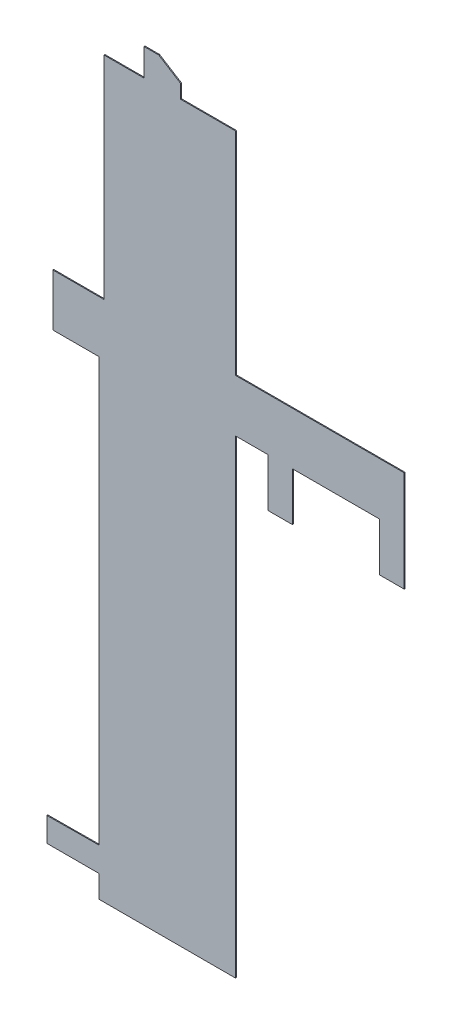
SolidWorks part; units mm, degrees
ref_plane "前视基准面" through (0, 0, 0) normal (0, 0, 1) x (1, 0, 0)
ref_plane "上视基准面" through (0, 0, 0) normal (0, 1, 0) x (1, 0, 0)
ref_plane "右视基准面" through (0, 0, 0) normal (1, 0, 0) x (0, 0, -1)
ref_plane "基准面4"
sketch "草图1" plane through (0, 0, 42) normal (0, 0, 1) x (1, 0, 0)
  line L0 (442.5, -384.2) -> (458.5, -384.2)
  line L1 (458.5, -384.2) -> (458.5, -354.2)
  line L2 (458.5, -354.2) -> (442.5, -354.2)
  line L3 (442.5, -354.2) -> (442.5, -384.2)
  line L4 (398.5, -384.2) -> (400.5, -384.2)
  line L5 (400.5, -384.2) -> (400.5, -354.2)
  line L6 (400.5, -354.2) -> (384.5, -354.2)
  line L7 (384.5, -354.2) -> (384.5, -384.2)
  line L8 (384.5, -384.2) -> (398.5, -384.2)
  line L9 (700.5, -673.6) -> (700.5, -726.6)
  line L10 (700.5, -726.6) -> (727.5, -726.6)
  line L11 (727.5, -726.6) -> (727.5, -673.6)
  line L12 (727.5, -673.6) -> (700.5, -673.6)
  line L13 (578, -673.6) -> (578, -726.6)
  line L14 (578, -726.6) -> (605, -726.6)
  line L15 (605, -726.6) -> (605, -673.6)
  line L16 (605, -673.6) -> (578, -673.6)
  line L17 (482.5, -443.7) -> (542.5, -443.7)
  line L18 (542.5, -443.7) -> (542.5, -413.6)
  line L19 (542.5, -413.6) -> (501.5, -413.6)
  line L20 (501.5, -413.6) -> (501.5, -423.1)
  line L21 (501.5, -423.1) -> (482.5, -423.1)
  line L22 (482.5, -423.1) -> (482.5, -443.7)
  line L23 (501.5, -413.6) -> (542.5, -413.6)
  line L24 (542.5, -413.6) -> (542.5, -384.2)
  line L25 (542.5, -384.2) -> (482.5, -384.2)
  line L26 (482.5, -384.2) -> (482.5, -410.1)
  line L27 (482.5, -410.1) -> (501.5, -410.1)
  line L28 (501.5, -410.1) -> (501.5, -413.6)
  line L29 (482.5, -498.7) -> (542.5, -498.7)
  line L30 (542.5, -498.7) -> (542.5, -443.7)
  line L31 (542.5, -443.7) -> (482.5, -443.7)
  line L32 (482.5, -443.7) -> (482.5, -498.7)
  line L33 (398.5, -499.2) -> (458.5, -499.2)
  line L34 (458.5, -499.2) -> (458.5, -441.7)
  line L35 (458.5, -441.7) -> (398.5, -441.7)
  line L36 (398.5, -441.7) -> (398.5, -499.2)
  line L37 (398.5, -441.7) -> (458.5, -441.7)
  line L38 (458.5, -441.7) -> (458.5, -384.2)
  line L39 (458.5, -384.2) -> (442.5, -384.2)
  line L40 (442.5, -384.2) -> (400.5, -384.2)
  line L41 (400.5, -384.2) -> (398.5, -384.2)
  line L42 (398.5, -384.2) -> (398.5, -441.7)
  line L43 (398.5, -616.2) -> (458.5, -616.2)
  line L44 (458.5, -616.2) -> (458.5, -499.2)
  line L45 (458.5, -499.2) -> (398.5, -499.2)
  line L46 (398.5, -499.2) -> (398.5, -616.2)
  line L47 (542.5, -616.2) -> (542.5, -498.7)
  line L48 (542.5, -498.7) -> (482.5, -498.7)
  line L49 (482.5, -498.7) -> (482.5, -616.2)
  line L50 (482.5, -616.2) -> (542.5, -616.2)
  line L51 (542.5, -1127.7) -> (417, -1127.7)
  line L52 (417, -1127.7) -> (417, -1188.1)
  line L53 (417, -1188.1) -> (542.5, -1188.1)
  line L54 (542.5, -1188.1) -> (542.5, -1127.7)
  line L55 (542.5, -786.2) -> (417.2959, -786.2)
  line L56 (417.2959, -786.2) -> (417, -896.8)
  line L57 (417, -896.8) -> (542.5, -896.8)
  line L58 (542.5, -896.8) -> (542.5, -786.2)
  line L59 (393, -673.2) -> (393, -1136.7)
  line L60 (393, -1136.7) -> (336, -1137.1)
  line L61 (336, -1137.1) -> (336, -1163.6)
  line L62 (336, -1163.6) -> (393, -1163.6)
  line L63 (393, -1163.6) -> (393, -1188.1)
  line L64 (393, -1188.1) -> (417, -1188.1)
  line L65 (417, -1188.1) -> (417, -1127.7)
  line L66 (417, -1127.7) -> (417, -896.8)
  line L67 (417, -896.8) -> (417.2959, -786.2)
  line L68 (417.2959, -786.2) -> (417.5981, -673.2658)
  line L69 (417.5981, -673.2658) -> (393, -673.2)
  line L70 (417.5981, -673.2658) -> (417.2959, -786.2)
  line L71 (417.2959, -786.2) -> (542.5, -786.2)
  line L72 (542.5, -786.2) -> (542.5, -673.6)
  line L73 (542.5, -673.6) -> (417.5981, -673.2658)
  line L74 (542.5, -896.8) -> (417, -896.8)
  line L75 (417, -896.8) -> (417, -1127.7)
  line L76 (417, -1127.7) -> (542.5, -1127.7)
  line L77 (542.5, -1127.7) -> (542.5, -896.8)
  line L78 (342.5, -616.2) -> (192.5, -616.2)
  line L79 (192.5, -616.2) -> (146.7, -616.2)
  line L80 (146.7, -616.2) -> (146.7, -566.2)
  line L81 (146.7, -566.2) -> (142.9, -566.2)
  line L82 (142.9, -566.2) -> (83.4, -566.2)
  line L83 (83.4, -566.2) -> (83.4, -463)
  line L84 (83.4, -463) -> (83.4, -379.5)
  line L85 (83.4, -379.5) -> (83.4, -276.5)
  line L86 (83.4, -276.5) -> (83.4, -137.6)
  line L87 (83.4, -137.6) -> (118.4, -137.6)
  line L88 (118.4, -137.6) -> (118.4, -79.7)
  line L89 (118.4, -79.7) -> (83.4, -79.7)
  line L90 (83.4, -79.7) -> (83.4, -23.7)
  line L91 (83.4, -23.7) -> (118.4, -23.7)
  line L92 (118.4, -23.7) -> (118.4, 0)
  line L93 (118.4, 0) -> (60, 0)
  line L94 (60, 0) -> (60, -80.6)
  line L95 (60, -80.6) -> (60, -191.9)
  line L96 (60, -191.9) -> (60, -276.5)
  line L97 (60, -276.5) -> (60, -335.9)
  line L98 (60, -335.9) -> (60, -420.6)
  line L99 (60, -420.6) -> (60, -550.6)
  line L100 (60, -550.6) -> (60, -677.8)
  line L101 (60, -677.8) -> (60, -782.9)
  line L102 (60, -782.9) -> (60, -839.5)
  line L103 (60, -839.5) -> (60, -923.6)
  line L104 (60, -923.6) -> (60, -1007.7)
  line L105 (60, -1007.7) -> (60, -1091.2)
  line L106 (60, -1091.2) -> (60, -1169.8)
  line L107 (60, -1169.8) -> (188.1, -1169.8)
  line L108 (188.1, -1169.8) -> (188.1, -1163.6)
  line L109 (188.1, -1163.6) -> (188.1, -1137.1)
  line L110 (188.1, -1137.1) -> (336, -1137.1)
  line L111 (336, -1137.1) -> (393, -1136.7)
  line L112 (393, -1136.7) -> (393, -673.2)
  line L113 (393, -673.2) -> (417.5981, -673.2658)
  line L114 (417.5981, -673.2658) -> (542.5, -673.6)
  line L115 (542.5, -673.6) -> (578, -673.6)
  line L116 (578, -673.6) -> (605, -673.6)
  line L117 (605, -673.6) -> (700.5, -673.6)
  line L118 (700.5, -673.6) -> (727.5, -673.6)
  line L119 (727.5, -673.6) -> (727.5, -616.2)
  line L120 (727.5, -616.2) -> (542.5, -616.2)
  line L121 (542.5, -616.2) -> (482.5, -616.2)
  line L122 (482.5, -616.2) -> (482.5, -498.7)
  line L123 (482.5, -498.7) -> (482.5, -443.7)
  line L124 (482.5, -443.7) -> (482.5, -423.1)
  line L125 (482.5, -423.1) -> (501.5, -423.1)
  line L126 (501.5, -423.1) -> (501.5, -413.6)
  line L127 (501.5, -413.6) -> (501.5, -410.1)
  line L128 (501.5, -410.1) -> (482.5, -410.1)
  line L129 (482.5, -410.1) -> (482.5, -384.2)
  line L130 (482.5, -384.2) -> (482.5, -369.2)
  line L131 (482.5, -369.2) -> (458.5, -354.2)
  line L132 (458.5, -354.2) -> (458.5, -384.2)
  line L133 (458.5, -384.2) -> (458.5, -441.7)
  line L134 (458.5, -441.7) -> (458.5, -499.2)
  line L135 (458.5, -499.2) -> (458.5, -616.2)
  line L136 (458.5, -616.2) -> (398.5, -616.2)
  line L137 (398.5, -616.2) -> (342.5, -616.2)
  line L138 (342.5, -673.2) -> (342.5, -616.2)
  line L139 (342.5, -616.2) -> (192.5, -616.2)
  line L140 (192.5, -616.2) -> (146.7, -616.2)
  line L141 (146.7, -616.2) -> (146.7, -566.2)
  line L142 (146.7, -566.2) -> (142.9, -566.2)
  line L143 (142.9, -566.2) -> (83.4, -566.2)
  line L144 (83.4, -566.2) -> (83.4, -463)
  line L145 (83.4, -463) -> (83.4, -379.5)
  line L146 (83.4, -379.5) -> (83.4, -276.5)
  line L147 (83.4, -276.5) -> (83.4, -137.6)
  line L148 (83.4, -137.6) -> (118.4, -137.6)
  line L149 (118.4, -137.6) -> (118.4, -79.7)
  line L150 (118.4, -79.7) -> (83.4, -79.7)
  line L151 (83.4, -79.7) -> (83.4, -23.7)
  line L152 (83.4, -23.7) -> (118.4, -23.7)
  line L153 (118.4, -23.7) -> (118.4, 0)
  line L154 (118.4, 0) -> (60, 0)
  line L155 (60, 0) -> (60, -80.6)
  line L156 (60, -80.6) -> (60, -191.9)
  line L157 (60, -191.9) -> (60, -276.5)
  line L158 (60, -276.5) -> (60, -335.9)
  line L159 (60, -335.9) -> (60, -420.6)
  line L160 (60, -420.6) -> (60, -550.6)
  line L161 (60, -550.6) -> (60, -677.8)
  line L162 (60, -677.8) -> (60, -782.9)
  line L163 (60, -782.9) -> (60, -839.5)
  line L164 (60, -839.5) -> (60, -923.6)
  line L165 (60, -923.6) -> (60, -1007.7)
  line L166 (60, -1007.7) -> (60, -1091.2)
  line L167 (60, -1091.2) -> (60, -1169.8)
  line L168 (60, -1169.8) -> (188.1, -1169.8)
  line L169 (188.1, -1169.8) -> (188.1, -1163.6)
  line L170 (188.1, -1163.6) -> (188.1, -1137.1)
  line L171 (188.1, -1137.1) -> (336, -1137.1)
  line L172 (336, -1137.1) -> (393, -1136.7)
  line L173 (393, -1136.7) -> (393, -673.2)
  line L174 (393, -673.2) -> (342.5, -673.2)
  dimension "D1" = 60
  dimension "D2" = 58.4
  dimension "D3" = 23.7
  dimension "D4" = 35
  dimension "D5" = 56
  dimension "D6" = 57.9
  dimension "D7" = 35
  dimension "D8" = 138.9
  dimension "D9" = 59.5
  dimension "D10" = 3.8
  dimension "D11" = 50
  dimension "D12" = 45.8
  dimension "D13" = 150
  dimension "D14" = 57
  dimension "D15" = 128.1
  dimension "D16" = 147.9
  dimension "D17" = 56
  dimension "D18" = 50.5
  dimension "D19" = 463.5
  dimension "D20" = 24.5
  dimension "D21" = 24
  dimension "D22" = 125.5
  dimension "D23" = 60.4
  dimension "D24" = 230.9
  dimension "D25" = 110.6
  dimension "D26" = 112.6
  dimension "D27" = 117
  dimension "D28" = 115
  dimension "D29" = 60
  dimension "D30" = 30
  dimension "D31" = 28.3019
  dimension "D32" = 28.3019
  dimension "D33" = 60
  dimension "D34" = 29.4
  dimension "D35" = 30.1
  dimension "D36" = 55
  dimension "D37" = 19
  dimension "D38" = 13
  dimension "D39" = 3.5
  dimension "D40" = 185
  dimension "D41" = 53
  dimension "D42" = 27
  dimension "D43" = 53
  dimension "D44" = 27
  dimension "D45" = 35.5
  dimension "D46" = 30
  dimension "D47" = 14
  dimension "D48" = 30
  dimension "D49" = 16
  dimension "D50" = 16
extrude "拉伸1" add sketch "草图1" against normal blind 1 contours L2 L3 L0 L1 | L7 L8 L4 L5 L6 | L11 L12 L9 L10 | L15 L16 L13 L14 | L21 L22 L17 L18 L19 L20 | L27 L28 L19 L24 L25 L26 | L17 L32 L29 L30 | L35 L36 L33 L34 | L4 L42 L35 L38 L0 L40 | L33 L46 L43 L44 | L49 L50 L47 L29 | L53 L54 L51 L52 | L57 L58 L55 L56 | L68 L69 L59 L60 L61 L62 L63 L64 L52 L66 L56 | L72 L73 L68 L55 | L51 L77 L57 L66 | L174 L69 L73 L115 L16 L117 L12 L119 L120 L50 L49 L32 L22 L21 L20 L28 L27 L26 L130 L131 L1 L38 L34 L44 L43 L137 L138
ref_plane "基准面5"
sketch "草图2" plane through (0, 0, 42) normal (0, 0, 1) x (1, 0, 0)
  line L0 (384.5, -354.2) -> (400.5, -354.2)
  line L1 (400.5, -354.2) -> (400.5, -384.2)
  line L2 (400.5, -384.2) -> (384.5, -384.2)
  line L3 (384.5, -384.2) -> (384.5, -354.2)
extrude "拉伸2" cut sketch "草图2" against normal blind 10
